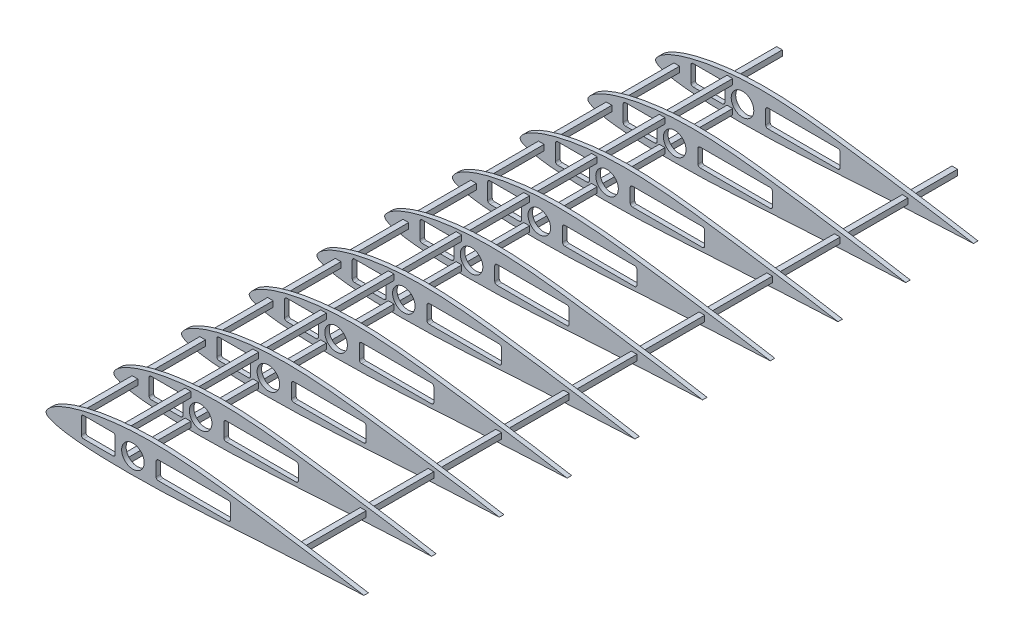
SolidWorks part; units mm, degrees
ref_plane "Front Plane" through (0, 0, 0) normal (0, 0, 1) x (1, 0, 0)
ref_plane "Top Plane" through (0, 0, 0) normal (0, 1, 0) x (1, 0, 0)
ref_plane "Right Plane" through (0, 0, 0) normal (1, 0, 0) x (0, 0, -1)
curve "Curve1"
  spline degree 3 poles (25.2088, 0.0031, 0) (25.4484, -0.0031, 0) (25.2117, 0.0209, 0) (25.0251, 0.0571, 0) (24.5852, 0.1328, 0) (24.06, 0.2322, 0) (23.3873, 0.3478, 0) (22.6018, 0.4739, 0) (21.7032, 0.6151, 0) (20.7068, 0.7694, 0) (19.6256, 0.9351, 0) (18.475, 1.1087, 0) (17.2708, 1.2865, 0) (16.0292, 1.4651, 0) (14.7666, 1.6379, 0) (13.5001, 1.8004, 0) (12.2446, 1.9439, 0) (11.0116, 2.0561, 0) (9.8099, 2.1301, 0) (8.6464, 2.1619, 0) (7.5276, 2.1493, 0) (6.459, 2.093, 0) (5.4467, 1.9949, 0) (4.4976, 1.8641, 0) (3.6202, 1.7053, 0) (2.8233, 1.523, 0) (2.1144, 1.3219, 0) (1.5008, 1.1059, 0) (0.9865, 0.8803, 0) (0.5779, 0.652, 0) (0.2708, 0.4245, 0) (0.0836, 0.2161, 0) (-0.0349, 0.004, 0) (0.089, -0.2027, 0) (0.3409, -0.3252, 0) (0.701, -0.4662, 0) (1.1913, -0.581, 0) (1.8002, -0.6841, 0) (2.5267, -0.768, 0) (3.3632, -0.8336, 0) (4.3022, -0.8807, 0) (5.334, -0.9092, 0) (6.4474, -0.9203, 0) (7.6302, -0.9134, 0) (8.8703, -0.8889, 0) (10.1572, -0.841, 0) (11.4808, -0.7741, 0) (12.8288, -0.6974, 0) (14.1854, -0.6164, 0) (15.5332, -0.5343, 0) (16.8545, -0.4545, 0) (18.1325, -0.3787, 0) (19.3501, -0.3089, 0) (20.4916, -0.2458, 0) (21.5411, -0.1904, 0) (22.4855, -0.1429, 0) (23.3092, -0.1017, 0) (24.0133, -0.0644, 0) (24.5612, -0.0287, 0) (25.0167, -0.0091, 0) (25.2088, 0.0031, 0) (25.4484, -0.0031, 0) (25.2117, 0.0209, 0) knots -0.015092 -0.006889 -0.001754 0 0.001748 0.006827 0.01488 0.025572 0.038694 0.054171 0.071834 0.091435 0.112685 0.135293 0.158944 0.183315 0.20807 0.232879 0.257399 0.281384 0.304706 0.327241 0.348897 0.369607 0.389308 0.407886 0.425177 0.441027 0.4553 0.467904 0.478752 0.487814 0.49509 0.500617 0.504451 0.507804 0.513091 0.520546 0.530249 0.542214 0.556382 0.572656 0.590895 0.610925 0.632536 0.655496 0.679547 0.704499 0.730211 0.756436 0.782837 0.809062 0.834776 0.859641 0.883338 0.905541 0.925965 0.944326 0.960366 0.973929 0.984908 0.993111 0.998246 1 1.001748 1.006827 1.01488 periodic
sketch "Sketch1" plane through (0, 0, 0) normal (0, 0, 1) x (1, 0, 0)
  line L0 (357.6496, 0) -> (0, 0) construction
  line L1 (0, 0) -> (0, 5.0209) construction
  spline S1 degree 3 poles (354.9573, 0.0431) (358.3317, -0.0432) (354.9981, 0.2938) (352.3707, 0.8024) (346.1763, 1.8676) (338.7813, 3.2655) (329.3081, 4.8919) (318.2482, 6.6648) (305.5952, 8.6507) (291.564, 10.8193) (276.34, 13.1505) (260.1392, 15.5903) (243.1815, 18.0913) (225.699, 20.6027) (207.9209, 23.0318) (190.087, 25.3152) (172.4086, 27.3328) (155.0467, 28.9096) (138.1258, 29.947) (121.7437, 30.3922) (105.9899, 30.2108) (90.9433, 29.4155) (76.6903, 28.0308) (63.3272, 26.1868) (50.9728, 23.9485) (39.7523, 21.3791) (29.7714, 18.545) (21.1318, 15.5018) (13.8914, 12.3237) (8.1391, 9.1075) (3.8158, 5.9031) (1.1802, 2.9693) (-0.4877, -0.018) (1.2572, -2.9285) (4.805, -4.6528) (9.8754, -6.6365) (16.78, -8.2511) (25.3535, -9.7017) (35.5828, -10.8813) (47.3622, -11.8027) (60.5842, -12.4624) (75.1117, -12.8607) (90.7897, -13.0132) (107.4435, -12.9137) (124.9052, -12.5651) (143.0256, -11.8868) (161.6617, -10.9405) (180.6424, -9.8572) (199.7442, -8.7119) (218.721, -7.5525) (237.3263, -6.4253) (255.3201, -5.3536) (272.4652, -4.367) (288.5372, -3.4753) (303.3148, -2.6922) (316.6121, -2.0207) (328.2104, -1.4385) (338.1246, -0.9102) (345.8395, -0.4061) (352.2525, -0.129) (354.9573, 0.0431) (358.3317, -0.0432) (354.9981, 0.2938) knots -0.015092 -0.006889 -0.001754 0 0.001748 0.006827 0.01488 0.025572 0.038694 0.054171 0.071834 0.091435 0.112685 0.135293 0.158944 0.183315 0.20807 0.232879 0.257399 0.281384 0.304706 0.327241 0.348897 0.369607 0.389308 0.407886 0.425177 0.441027 0.4553 0.467904 0.478752 0.487814 0.49509 0.500617 0.504451 0.507804 0.513091 0.520546 0.530249 0.542214 0.556382 0.572656 0.590895 0.610925 0.632536 0.655496 0.679547 0.704499 0.730211 0.756436 0.782837 0.809062 0.834776 0.859641 0.883338 0.905541 0.925965 0.944326 0.960366 0.973929 0.984908 0.993111 0.998246 1 1.001748 1.006827 1.01488 only from (357.6496, 0) to (357.6496, 0)
  dimension "D1" = 357.6496
ref_plane "Plane3" through (0, 0, 76.2) normal (0, 0, 1) x (1, 0, 0)
ref_plane "Plane4" through (0, 0, 152.4) normal (0, 0, 1) x (1, 0, 0)
ref_plane "Plane5" through (0, 0, 228.6) normal (0, 0, 1) x (1, 0, 0)
ref_plane "Plane6" through (0, 0, 304.8) normal (0, 0, 1) x (1, 0, 0)
ref_plane "Plane7" through (0, 0, 381) normal (0, 0, 1) x (1, 0, 0)
ref_plane "Plane8" through (0, 0, 457.2) normal (0, 0, 1) x (1, 0, 0)
ref_plane "Plane9" through (0, 0, 533.4) normal (0, 0, 1) x (1, 0, 0)
ref_plane "Plane10" through (0, 0, 609.6) normal (0, 0, 1) x (1, 0, 0)
ref_plane "Plane11" through (0, 0, 685.8) normal (0, 0, 1) x (1, 0, 0)
sketch "Sketch5" plane through (0, 0, 76.2) normal (0, 0, 1) x (1, 0, 0)
  spline S0 degree 3 poles (354.9573, 0.0431) (358.3317, -0.0432) (354.9981, 0.2938) (352.3707, 0.8024) (346.1763, 1.8676) (338.7813, 3.2655) (329.3081, 4.8919) (318.2482, 6.6648) (305.5952, 8.6507) (291.564, 10.8193) (276.34, 13.1505) (260.1392, 15.5903) (243.1815, 18.0913) (225.699, 20.6027) (207.9209, 23.0318) (190.087, 25.3152) (172.4086, 27.3328) (155.0467, 28.9096) (138.1258, 29.947) (121.7437, 30.3922) (105.9899, 30.2108) (90.9433, 29.4155) (76.6903, 28.0308) (63.3272, 26.1868) (50.9728, 23.9485) (39.7523, 21.3791) (29.7714, 18.545) (21.1318, 15.5018) (13.8914, 12.3237) (8.1391, 9.1075) (3.8158, 5.9031) (1.1802, 2.9693) (-0.4877, -0.018) (1.2572, -2.9285) (4.805, -4.6528) (9.8754, -6.6365) (16.78, -8.2511) (25.3535, -9.7017) (35.5828, -10.8813) (47.3622, -11.8027) (60.5842, -12.4624) (75.1117, -12.8607) (90.7897, -13.0132) (107.4435, -12.9137) (124.9052, -12.5651) (143.0256, -11.8868) (161.6617, -10.9405) (180.6424, -9.8572) (199.7442, -8.7119) (218.721, -7.5525) (237.3263, -6.4253) (255.3201, -5.3536) (272.4652, -4.367) (288.5372, -3.4753) (303.3148, -2.6922) (316.6121, -2.0207) (328.2104, -1.4385) (338.1246, -0.9102) (345.8395, -0.4061) (352.2525, -0.129) (354.9573, 0.0431) (358.3317, -0.0432) (354.9981, 0.2938) knots -0.015092 -0.006889 -0.001754 0 0.001748 0.006827 0.01488 0.025572 0.038694 0.054171 0.071834 0.091435 0.112685 0.135293 0.158944 0.183315 0.20807 0.232879 0.257399 0.281384 0.304706 0.327241 0.348897 0.369607 0.389308 0.407886 0.425177 0.441027 0.4553 0.467904 0.478752 0.487814 0.49509 0.500617 0.504451 0.507804 0.513091 0.520546 0.530249 0.542214 0.556382 0.572656 0.590895 0.610925 0.632536 0.655496 0.679547 0.704499 0.730211 0.756436 0.782837 0.809062 0.834776 0.859641 0.883338 0.905541 0.925965 0.944326 0.960366 0.973929 0.984908 0.993111 0.998246 1 1.001748 1.006827 1.01488 only from (357.6496, 0) to (357.6496, 0) construction
  spline S1 degree 3 poles (354.9573, 0.0431) (358.3317, -0.0432) (354.9981, 0.2938) (352.3707, 0.8024) (346.1763, 1.8676) (338.7813, 3.2655) (329.3081, 4.8919) (318.2482, 6.6648) (305.5952, 8.6507) (291.564, 10.8193) (276.34, 13.1505) (260.1392, 15.5903) (243.1815, 18.0913) (225.699, 20.6027) (207.9209, 23.0318) (190.087, 25.3152) (172.4086, 27.3328) (155.0467, 28.9096) (138.1258, 29.947) (121.7437, 30.3922) (105.9899, 30.2108) (90.9433, 29.4155) (76.6903, 28.0308) (63.3272, 26.1868) (50.9728, 23.9485) (39.7523, 21.3791) (29.7714, 18.545) (21.1318, 15.5018) (13.8914, 12.3237) (8.1391, 9.1075) (3.8158, 5.9031) (1.1802, 2.9693) (-0.4877, -0.018) (1.2572, -2.9285) (4.805, -4.6528) (9.8754, -6.6365) (16.78, -8.2511) (25.3535, -9.7017) (35.5828, -10.8813) (47.3622, -11.8027) (60.5842, -12.4624) (75.1117, -12.8607) (90.7897, -13.0132) (107.4435, -12.9137) (124.9052, -12.5651) (143.0256, -11.8868) (161.6617, -10.9405) (180.6424, -9.8572) (199.7442, -8.7119) (218.721, -7.5525) (237.3263, -6.4253) (255.3201, -5.3536) (272.4652, -4.367) (288.5372, -3.4753) (303.3148, -2.6922) (316.6121, -2.0207) (328.2104, -1.4385) (338.1246, -0.9102) (345.8395, -0.4061) (352.2525, -0.129) (354.9573, 0.0431) (358.3317, -0.0432) (354.9981, 0.2938) knots -0.015092 -0.006889 -0.001754 0 0.001748 0.006827 0.01488 0.025572 0.038694 0.054171 0.071834 0.091435 0.112685 0.135293 0.158944 0.183315 0.20807 0.232879 0.257399 0.281384 0.304706 0.327241 0.348897 0.369607 0.389308 0.407886 0.425177 0.441027 0.4553 0.467904 0.478752 0.487814 0.49509 0.500617 0.504451 0.507804 0.513091 0.520546 0.530249 0.542214 0.556382 0.572656 0.590895 0.610925 0.632536 0.655496 0.679547 0.704499 0.730211 0.756436 0.782837 0.809062 0.834776 0.859641 0.883338 0.905541 0.925965 0.944326 0.960366 0.973929 0.984908 0.993111 0.998246 1 1.001748 1.006827 1.01488 only from (357.6496, 0) to (357.6496, 0)
sketch "Sketch6" plane through (0, 0, 152.4) normal (0, 0, 1) x (1, 0, 0)
  spline S0 degree 3 poles (354.9573, 0.0431) (358.3317, -0.0432) (354.9981, 0.2938) (352.3707, 0.8024) (346.1763, 1.8676) (338.7813, 3.2655) (329.3081, 4.8919) (318.2482, 6.6648) (305.5952, 8.6507) (291.564, 10.8193) (276.34, 13.1505) (260.1392, 15.5903) (243.1815, 18.0913) (225.699, 20.6027) (207.9209, 23.0318) (190.087, 25.3152) (172.4086, 27.3328) (155.0467, 28.9096) (138.1258, 29.947) (121.7437, 30.3922) (105.9899, 30.2108) (90.9433, 29.4155) (76.6903, 28.0308) (63.3272, 26.1868) (50.9728, 23.9485) (39.7523, 21.3791) (29.7714, 18.545) (21.1318, 15.5018) (13.8914, 12.3237) (8.1391, 9.1075) (3.8158, 5.9031) (1.1802, 2.9693) (-0.4877, -0.018) (1.2572, -2.9285) (4.805, -4.6528) (9.8754, -6.6365) (16.78, -8.2511) (25.3535, -9.7017) (35.5828, -10.8813) (47.3622, -11.8027) (60.5842, -12.4624) (75.1117, -12.8607) (90.7897, -13.0132) (107.4435, -12.9137) (124.9052, -12.5651) (143.0256, -11.8868) (161.6617, -10.9405) (180.6424, -9.8572) (199.7442, -8.7119) (218.721, -7.5525) (237.3263, -6.4253) (255.3201, -5.3536) (272.4652, -4.367) (288.5372, -3.4753) (303.3148, -2.6922) (316.6121, -2.0207) (328.2104, -1.4385) (338.1246, -0.9102) (345.8395, -0.4061) (352.2525, -0.129) (354.9573, 0.0431) (358.3317, -0.0432) (354.9981, 0.2938) knots -0.015092 -0.006889 -0.001754 0 0.001748 0.006827 0.01488 0.025572 0.038694 0.054171 0.071834 0.091435 0.112685 0.135293 0.158944 0.183315 0.20807 0.232879 0.257399 0.281384 0.304706 0.327241 0.348897 0.369607 0.389308 0.407886 0.425177 0.441027 0.4553 0.467904 0.478752 0.487814 0.49509 0.500617 0.504451 0.507804 0.513091 0.520546 0.530249 0.542214 0.556382 0.572656 0.590895 0.610925 0.632536 0.655496 0.679547 0.704499 0.730211 0.756436 0.782837 0.809062 0.834776 0.859641 0.883338 0.905541 0.925965 0.944326 0.960366 0.973929 0.984908 0.993111 0.998246 1 1.001748 1.006827 1.01488 only from (357.6496, 0) to (357.6496, 0) construction
  spline S1 degree 3 poles (354.9573, 0.0431) (358.3317, -0.0432) (354.9981, 0.2938) (352.3707, 0.8024) (346.1763, 1.8676) (338.7813, 3.2655) (329.3081, 4.8919) (318.2482, 6.6648) (305.5952, 8.6507) (291.564, 10.8193) (276.34, 13.1505) (260.1392, 15.5903) (243.1815, 18.0913) (225.699, 20.6027) (207.9209, 23.0318) (190.087, 25.3152) (172.4086, 27.3328) (155.0467, 28.9096) (138.1258, 29.947) (121.7437, 30.3922) (105.9899, 30.2108) (90.9433, 29.4155) (76.6903, 28.0308) (63.3272, 26.1868) (50.9728, 23.9485) (39.7523, 21.3791) (29.7714, 18.545) (21.1318, 15.5018) (13.8914, 12.3237) (8.1391, 9.1075) (3.8158, 5.9031) (1.1802, 2.9693) (-0.4877, -0.018) (1.2572, -2.9285) (4.805, -4.6528) (9.8754, -6.6365) (16.78, -8.2511) (25.3535, -9.7017) (35.5828, -10.8813) (47.3622, -11.8027) (60.5842, -12.4624) (75.1117, -12.8607) (90.7897, -13.0132) (107.4435, -12.9137) (124.9052, -12.5651) (143.0256, -11.8868) (161.6617, -10.9405) (180.6424, -9.8572) (199.7442, -8.7119) (218.721, -7.5525) (237.3263, -6.4253) (255.3201, -5.3536) (272.4652, -4.367) (288.5372, -3.4753) (303.3148, -2.6922) (316.6121, -2.0207) (328.2104, -1.4385) (338.1246, -0.9102) (345.8395, -0.4061) (352.2525, -0.129) (354.9573, 0.0431) (358.3317, -0.0432) (354.9981, 0.2938) knots -0.015092 -0.006889 -0.001754 0 0.001748 0.006827 0.01488 0.025572 0.038694 0.054171 0.071834 0.091435 0.112685 0.135293 0.158944 0.183315 0.20807 0.232879 0.257399 0.281384 0.304706 0.327241 0.348897 0.369607 0.389308 0.407886 0.425177 0.441027 0.4553 0.467904 0.478752 0.487814 0.49509 0.500617 0.504451 0.507804 0.513091 0.520546 0.530249 0.542214 0.556382 0.572656 0.590895 0.610925 0.632536 0.655496 0.679547 0.704499 0.730211 0.756436 0.782837 0.809062 0.834776 0.859641 0.883338 0.905541 0.925965 0.944326 0.960366 0.973929 0.984908 0.993111 0.998246 1 1.001748 1.006827 1.01488 only from (357.6496, 0) to (357.6496, 0)
sketch "Sketch7" plane through (0, 0, 228.6) normal (0, 0, 1) x (1, 0, 0)
  spline S0 degree 3 poles (354.9573, 0.0431) (358.3317, -0.0432) (354.9981, 0.2938) (352.3707, 0.8024) (346.1763, 1.8676) (338.7813, 3.2655) (329.3081, 4.8919) (318.2482, 6.6648) (305.5952, 8.6507) (291.564, 10.8193) (276.34, 13.1505) (260.1392, 15.5903) (243.1815, 18.0913) (225.699, 20.6027) (207.9209, 23.0318) (190.087, 25.3152) (172.4086, 27.3328) (155.0467, 28.9096) (138.1258, 29.947) (121.7437, 30.3922) (105.9899, 30.2108) (90.9433, 29.4155) (76.6903, 28.0308) (63.3272, 26.1868) (50.9728, 23.9485) (39.7523, 21.3791) (29.7714, 18.545) (21.1318, 15.5018) (13.8914, 12.3237) (8.1391, 9.1075) (3.8158, 5.9031) (1.1802, 2.9693) (-0.4877, -0.018) (1.2572, -2.9285) (4.805, -4.6528) (9.8754, -6.6365) (16.78, -8.2511) (25.3535, -9.7017) (35.5828, -10.8813) (47.3622, -11.8027) (60.5842, -12.4624) (75.1117, -12.8607) (90.7897, -13.0132) (107.4435, -12.9137) (124.9052, -12.5651) (143.0256, -11.8868) (161.6617, -10.9405) (180.6424, -9.8572) (199.7442, -8.7119) (218.721, -7.5525) (237.3263, -6.4253) (255.3201, -5.3536) (272.4652, -4.367) (288.5372, -3.4753) (303.3148, -2.6922) (316.6121, -2.0207) (328.2104, -1.4385) (338.1246, -0.9102) (345.8395, -0.4061) (352.2525, -0.129) (354.9573, 0.0431) (358.3317, -0.0432) (354.9981, 0.2938) knots -0.015092 -0.006889 -0.001754 0 0.001748 0.006827 0.01488 0.025572 0.038694 0.054171 0.071834 0.091435 0.112685 0.135293 0.158944 0.183315 0.20807 0.232879 0.257399 0.281384 0.304706 0.327241 0.348897 0.369607 0.389308 0.407886 0.425177 0.441027 0.4553 0.467904 0.478752 0.487814 0.49509 0.500617 0.504451 0.507804 0.513091 0.520546 0.530249 0.542214 0.556382 0.572656 0.590895 0.610925 0.632536 0.655496 0.679547 0.704499 0.730211 0.756436 0.782837 0.809062 0.834776 0.859641 0.883338 0.905541 0.925965 0.944326 0.960366 0.973929 0.984908 0.993111 0.998246 1 1.001748 1.006827 1.01488 only from (357.6496, 0) to (357.6496, 0) construction
  spline S1 degree 3 poles (354.9573, 0.0431) (358.3317, -0.0432) (354.9981, 0.2938) (352.3707, 0.8024) (346.1763, 1.8676) (338.7813, 3.2655) (329.3081, 4.8919) (318.2482, 6.6648) (305.5952, 8.6507) (291.564, 10.8193) (276.34, 13.1505) (260.1392, 15.5903) (243.1815, 18.0913) (225.699, 20.6027) (207.9209, 23.0318) (190.087, 25.3152) (172.4086, 27.3328) (155.0467, 28.9096) (138.1258, 29.947) (121.7437, 30.3922) (105.9899, 30.2108) (90.9433, 29.4155) (76.6903, 28.0308) (63.3272, 26.1868) (50.9728, 23.9485) (39.7523, 21.3791) (29.7714, 18.545) (21.1318, 15.5018) (13.8914, 12.3237) (8.1391, 9.1075) (3.8158, 5.9031) (1.1802, 2.9693) (-0.4877, -0.018) (1.2572, -2.9285) (4.805, -4.6528) (9.8754, -6.6365) (16.78, -8.2511) (25.3535, -9.7017) (35.5828, -10.8813) (47.3622, -11.8027) (60.5842, -12.4624) (75.1117, -12.8607) (90.7897, -13.0132) (107.4435, -12.9137) (124.9052, -12.5651) (143.0256, -11.8868) (161.6617, -10.9405) (180.6424, -9.8572) (199.7442, -8.7119) (218.721, -7.5525) (237.3263, -6.4253) (255.3201, -5.3536) (272.4652, -4.367) (288.5372, -3.4753) (303.3148, -2.6922) (316.6121, -2.0207) (328.2104, -1.4385) (338.1246, -0.9102) (345.8395, -0.4061) (352.2525, -0.129) (354.9573, 0.0431) (358.3317, -0.0432) (354.9981, 0.2938) knots -0.015092 -0.006889 -0.001754 0 0.001748 0.006827 0.01488 0.025572 0.038694 0.054171 0.071834 0.091435 0.112685 0.135293 0.158944 0.183315 0.20807 0.232879 0.257399 0.281384 0.304706 0.327241 0.348897 0.369607 0.389308 0.407886 0.425177 0.441027 0.4553 0.467904 0.478752 0.487814 0.49509 0.500617 0.504451 0.507804 0.513091 0.520546 0.530249 0.542214 0.556382 0.572656 0.590895 0.610925 0.632536 0.655496 0.679547 0.704499 0.730211 0.756436 0.782837 0.809062 0.834776 0.859641 0.883338 0.905541 0.925965 0.944326 0.960366 0.973929 0.984908 0.993111 0.998246 1 1.001748 1.006827 1.01488 only from (357.6496, 0) to (357.6496, 0)
sketch "Sketch8" plane through (0, 0, 304.8) normal (0, 0, 1) x (1, 0, 0)
  spline S0 degree 3 poles (354.9573, 0.0431) (358.3317, -0.0432) (354.9981, 0.2938) (352.3707, 0.8024) (346.1763, 1.8676) (338.7813, 3.2655) (329.3081, 4.8919) (318.2482, 6.6648) (305.5952, 8.6507) (291.564, 10.8193) (276.34, 13.1505) (260.1392, 15.5903) (243.1815, 18.0913) (225.699, 20.6027) (207.9209, 23.0318) (190.087, 25.3152) (172.4086, 27.3328) (155.0467, 28.9096) (138.1258, 29.947) (121.7437, 30.3922) (105.9899, 30.2108) (90.9433, 29.4155) (76.6903, 28.0308) (63.3272, 26.1868) (50.9728, 23.9485) (39.7523, 21.3791) (29.7714, 18.545) (21.1318, 15.5018) (13.8914, 12.3237) (8.1391, 9.1075) (3.8158, 5.9031) (1.1802, 2.9693) (-0.4877, -0.018) (1.2572, -2.9285) (4.805, -4.6528) (9.8754, -6.6365) (16.78, -8.2511) (25.3535, -9.7017) (35.5828, -10.8813) (47.3622, -11.8027) (60.5842, -12.4624) (75.1117, -12.8607) (90.7897, -13.0132) (107.4435, -12.9137) (124.9052, -12.5651) (143.0256, -11.8868) (161.6617, -10.9405) (180.6424, -9.8572) (199.7442, -8.7119) (218.721, -7.5525) (237.3263, -6.4253) (255.3201, -5.3536) (272.4652, -4.367) (288.5372, -3.4753) (303.3148, -2.6922) (316.6121, -2.0207) (328.2104, -1.4385) (338.1246, -0.9102) (345.8395, -0.4061) (352.2525, -0.129) (354.9573, 0.0431) (358.3317, -0.0432) (354.9981, 0.2938) knots -0.015092 -0.006889 -0.001754 0 0.001748 0.006827 0.01488 0.025572 0.038694 0.054171 0.071834 0.091435 0.112685 0.135293 0.158944 0.183315 0.20807 0.232879 0.257399 0.281384 0.304706 0.327241 0.348897 0.369607 0.389308 0.407886 0.425177 0.441027 0.4553 0.467904 0.478752 0.487814 0.49509 0.500617 0.504451 0.507804 0.513091 0.520546 0.530249 0.542214 0.556382 0.572656 0.590895 0.610925 0.632536 0.655496 0.679547 0.704499 0.730211 0.756436 0.782837 0.809062 0.834776 0.859641 0.883338 0.905541 0.925965 0.944326 0.960366 0.973929 0.984908 0.993111 0.998246 1 1.001748 1.006827 1.01488 only from (357.6496, 0) to (357.6496, 0) construction
  spline S1 degree 3 poles (354.9573, 0.0431) (358.3317, -0.0432) (354.9981, 0.2938) (352.3707, 0.8024) (346.1763, 1.8676) (338.7813, 3.2655) (329.3081, 4.8919) (318.2482, 6.6648) (305.5952, 8.6507) (291.564, 10.8193) (276.34, 13.1505) (260.1392, 15.5903) (243.1815, 18.0913) (225.699, 20.6027) (207.9209, 23.0318) (190.087, 25.3152) (172.4086, 27.3328) (155.0467, 28.9096) (138.1258, 29.947) (121.7437, 30.3922) (105.9899, 30.2108) (90.9433, 29.4155) (76.6903, 28.0308) (63.3272, 26.1868) (50.9728, 23.9485) (39.7523, 21.3791) (29.7714, 18.545) (21.1318, 15.5018) (13.8914, 12.3237) (8.1391, 9.1075) (3.8158, 5.9031) (1.1802, 2.9693) (-0.4877, -0.018) (1.2572, -2.9285) (4.805, -4.6528) (9.8754, -6.6365) (16.78, -8.2511) (25.3535, -9.7017) (35.5828, -10.8813) (47.3622, -11.8027) (60.5842, -12.4624) (75.1117, -12.8607) (90.7897, -13.0132) (107.4435, -12.9137) (124.9052, -12.5651) (143.0256, -11.8868) (161.6617, -10.9405) (180.6424, -9.8572) (199.7442, -8.7119) (218.721, -7.5525) (237.3263, -6.4253) (255.3201, -5.3536) (272.4652, -4.367) (288.5372, -3.4753) (303.3148, -2.6922) (316.6121, -2.0207) (328.2104, -1.4385) (338.1246, -0.9102) (345.8395, -0.4061) (352.2525, -0.129) (354.9573, 0.0431) (358.3317, -0.0432) (354.9981, 0.2938) knots -0.015092 -0.006889 -0.001754 0 0.001748 0.006827 0.01488 0.025572 0.038694 0.054171 0.071834 0.091435 0.112685 0.135293 0.158944 0.183315 0.20807 0.232879 0.257399 0.281384 0.304706 0.327241 0.348897 0.369607 0.389308 0.407886 0.425177 0.441027 0.4553 0.467904 0.478752 0.487814 0.49509 0.500617 0.504451 0.507804 0.513091 0.520546 0.530249 0.542214 0.556382 0.572656 0.590895 0.610925 0.632536 0.655496 0.679547 0.704499 0.730211 0.756436 0.782837 0.809062 0.834776 0.859641 0.883338 0.905541 0.925965 0.944326 0.960366 0.973929 0.984908 0.993111 0.998246 1 1.001748 1.006827 1.01488 only from (357.6496, 0) to (357.6496, 0)
sketch "Sketch9" plane through (0, 0, 381) normal (0, 0, 1) x (1, 0, 0)
  spline S0 degree 3 poles (354.9573, 0.0431) (358.3317, -0.0432) (354.9981, 0.2938) (352.3707, 0.8024) (346.1763, 1.8676) (338.7813, 3.2655) (329.3081, 4.8919) (318.2482, 6.6648) (305.5952, 8.6507) (291.564, 10.8193) (276.34, 13.1505) (260.1392, 15.5903) (243.1815, 18.0913) (225.699, 20.6027) (207.9209, 23.0318) (190.087, 25.3152) (172.4086, 27.3328) (155.0467, 28.9096) (138.1258, 29.947) (121.7437, 30.3922) (105.9899, 30.2108) (90.9433, 29.4155) (76.6903, 28.0308) (63.3272, 26.1868) (50.9728, 23.9485) (39.7523, 21.3791) (29.7714, 18.545) (21.1318, 15.5018) (13.8914, 12.3237) (8.1391, 9.1075) (3.8158, 5.9031) (1.1802, 2.9693) (-0.4877, -0.018) (1.2572, -2.9285) (4.805, -4.6528) (9.8754, -6.6365) (16.78, -8.2511) (25.3535, -9.7017) (35.5828, -10.8813) (47.3622, -11.8027) (60.5842, -12.4624) (75.1117, -12.8607) (90.7897, -13.0132) (107.4435, -12.9137) (124.9052, -12.5651) (143.0256, -11.8868) (161.6617, -10.9405) (180.6424, -9.8572) (199.7442, -8.7119) (218.721, -7.5525) (237.3263, -6.4253) (255.3201, -5.3536) (272.4652, -4.367) (288.5372, -3.4753) (303.3148, -2.6922) (316.6121, -2.0207) (328.2104, -1.4385) (338.1246, -0.9102) (345.8395, -0.4061) (352.2525, -0.129) (354.9573, 0.0431) (358.3317, -0.0432) (354.9981, 0.2938) knots -0.015092 -0.006889 -0.001754 0 0.001748 0.006827 0.01488 0.025572 0.038694 0.054171 0.071834 0.091435 0.112685 0.135293 0.158944 0.183315 0.20807 0.232879 0.257399 0.281384 0.304706 0.327241 0.348897 0.369607 0.389308 0.407886 0.425177 0.441027 0.4553 0.467904 0.478752 0.487814 0.49509 0.500617 0.504451 0.507804 0.513091 0.520546 0.530249 0.542214 0.556382 0.572656 0.590895 0.610925 0.632536 0.655496 0.679547 0.704499 0.730211 0.756436 0.782837 0.809062 0.834776 0.859641 0.883338 0.905541 0.925965 0.944326 0.960366 0.973929 0.984908 0.993111 0.998246 1 1.001748 1.006827 1.01488 only from (357.6496, 0) to (357.6496, 0) construction
  spline S1 degree 3 poles (354.9573, 0.0431) (358.3317, -0.0432) (354.9981, 0.2938) (352.3707, 0.8024) (346.1763, 1.8676) (338.7813, 3.2655) (329.3081, 4.8919) (318.2482, 6.6648) (305.5952, 8.6507) (291.564, 10.8193) (276.34, 13.1505) (260.1392, 15.5903) (243.1815, 18.0913) (225.699, 20.6027) (207.9209, 23.0318) (190.087, 25.3152) (172.4086, 27.3328) (155.0467, 28.9096) (138.1258, 29.947) (121.7437, 30.3922) (105.9899, 30.2108) (90.9433, 29.4155) (76.6903, 28.0308) (63.3272, 26.1868) (50.9728, 23.9485) (39.7523, 21.3791) (29.7714, 18.545) (21.1318, 15.5018) (13.8914, 12.3237) (8.1391, 9.1075) (3.8158, 5.9031) (1.1802, 2.9693) (-0.4877, -0.018) (1.2572, -2.9285) (4.805, -4.6528) (9.8754, -6.6365) (16.78, -8.2511) (25.3535, -9.7017) (35.5828, -10.8813) (47.3622, -11.8027) (60.5842, -12.4624) (75.1117, -12.8607) (90.7897, -13.0132) (107.4435, -12.9137) (124.9052, -12.5651) (143.0256, -11.8868) (161.6617, -10.9405) (180.6424, -9.8572) (199.7442, -8.7119) (218.721, -7.5525) (237.3263, -6.4253) (255.3201, -5.3536) (272.4652, -4.367) (288.5372, -3.4753) (303.3148, -2.6922) (316.6121, -2.0207) (328.2104, -1.4385) (338.1246, -0.9102) (345.8395, -0.4061) (352.2525, -0.129) (354.9573, 0.0431) (358.3317, -0.0432) (354.9981, 0.2938) knots -0.015092 -0.006889 -0.001754 0 0.001748 0.006827 0.01488 0.025572 0.038694 0.054171 0.071834 0.091435 0.112685 0.135293 0.158944 0.183315 0.20807 0.232879 0.257399 0.281384 0.304706 0.327241 0.348897 0.369607 0.389308 0.407886 0.425177 0.441027 0.4553 0.467904 0.478752 0.487814 0.49509 0.500617 0.504451 0.507804 0.513091 0.520546 0.530249 0.542214 0.556382 0.572656 0.590895 0.610925 0.632536 0.655496 0.679547 0.704499 0.730211 0.756436 0.782837 0.809062 0.834776 0.859641 0.883338 0.905541 0.925965 0.944326 0.960366 0.973929 0.984908 0.993111 0.998246 1 1.001748 1.006827 1.01488 only from (357.6496, 0) to (357.6496, 0)
sketch "Sketch10" plane through (0, 0, 457.2) normal (0, 0, 1) x (1, 0, 0)
  spline S0 degree 3 poles (354.9573, 0.0431) (358.3317, -0.0432) (354.9981, 0.2938) (352.3707, 0.8024) (346.1763, 1.8676) (338.7813, 3.2655) (329.3081, 4.8919) (318.2482, 6.6648) (305.5952, 8.6507) (291.564, 10.8193) (276.34, 13.1505) (260.1392, 15.5903) (243.1815, 18.0913) (225.699, 20.6027) (207.9209, 23.0318) (190.087, 25.3152) (172.4086, 27.3328) (155.0467, 28.9096) (138.1258, 29.947) (121.7437, 30.3922) (105.9899, 30.2108) (90.9433, 29.4155) (76.6903, 28.0308) (63.3272, 26.1868) (50.9728, 23.9485) (39.7523, 21.3791) (29.7714, 18.545) (21.1318, 15.5018) (13.8914, 12.3237) (8.1391, 9.1075) (3.8158, 5.9031) (1.1802, 2.9693) (-0.4877, -0.018) (1.2572, -2.9285) (4.805, -4.6528) (9.8754, -6.6365) (16.78, -8.2511) (25.3535, -9.7017) (35.5828, -10.8813) (47.3622, -11.8027) (60.5842, -12.4624) (75.1117, -12.8607) (90.7897, -13.0132) (107.4435, -12.9137) (124.9052, -12.5651) (143.0256, -11.8868) (161.6617, -10.9405) (180.6424, -9.8572) (199.7442, -8.7119) (218.721, -7.5525) (237.3263, -6.4253) (255.3201, -5.3536) (272.4652, -4.367) (288.5372, -3.4753) (303.3148, -2.6922) (316.6121, -2.0207) (328.2104, -1.4385) (338.1246, -0.9102) (345.8395, -0.4061) (352.2525, -0.129) (354.9573, 0.0431) (358.3317, -0.0432) (354.9981, 0.2938) knots -0.015092 -0.006889 -0.001754 0 0.001748 0.006827 0.01488 0.025572 0.038694 0.054171 0.071834 0.091435 0.112685 0.135293 0.158944 0.183315 0.20807 0.232879 0.257399 0.281384 0.304706 0.327241 0.348897 0.369607 0.389308 0.407886 0.425177 0.441027 0.4553 0.467904 0.478752 0.487814 0.49509 0.500617 0.504451 0.507804 0.513091 0.520546 0.530249 0.542214 0.556382 0.572656 0.590895 0.610925 0.632536 0.655496 0.679547 0.704499 0.730211 0.756436 0.782837 0.809062 0.834776 0.859641 0.883338 0.905541 0.925965 0.944326 0.960366 0.973929 0.984908 0.993111 0.998246 1 1.001748 1.006827 1.01488 only from (357.6496, 0) to (357.6496, 0) construction
  spline S1 degree 3 poles (354.9573, 0.0431) (358.3317, -0.0432) (354.9981, 0.2938) (352.3707, 0.8024) (346.1763, 1.8676) (338.7813, 3.2655) (329.3081, 4.8919) (318.2482, 6.6648) (305.5952, 8.6507) (291.564, 10.8193) (276.34, 13.1505) (260.1392, 15.5903) (243.1815, 18.0913) (225.699, 20.6027) (207.9209, 23.0318) (190.087, 25.3152) (172.4086, 27.3328) (155.0467, 28.9096) (138.1258, 29.947) (121.7437, 30.3922) (105.9899, 30.2108) (90.9433, 29.4155) (76.6903, 28.0308) (63.3272, 26.1868) (50.9728, 23.9485) (39.7523, 21.3791) (29.7714, 18.545) (21.1318, 15.5018) (13.8914, 12.3237) (8.1391, 9.1075) (3.8158, 5.9031) (1.1802, 2.9693) (-0.4877, -0.018) (1.2572, -2.9285) (4.805, -4.6528) (9.8754, -6.6365) (16.78, -8.2511) (25.3535, -9.7017) (35.5828, -10.8813) (47.3622, -11.8027) (60.5842, -12.4624) (75.1117, -12.8607) (90.7897, -13.0132) (107.4435, -12.9137) (124.9052, -12.5651) (143.0256, -11.8868) (161.6617, -10.9405) (180.6424, -9.8572) (199.7442, -8.7119) (218.721, -7.5525) (237.3263, -6.4253) (255.3201, -5.3536) (272.4652, -4.367) (288.5372, -3.4753) (303.3148, -2.6922) (316.6121, -2.0207) (328.2104, -1.4385) (338.1246, -0.9102) (345.8395, -0.4061) (352.2525, -0.129) (354.9573, 0.0431) (358.3317, -0.0432) (354.9981, 0.2938) knots -0.015092 -0.006889 -0.001754 0 0.001748 0.006827 0.01488 0.025572 0.038694 0.054171 0.071834 0.091435 0.112685 0.135293 0.158944 0.183315 0.20807 0.232879 0.257399 0.281384 0.304706 0.327241 0.348897 0.369607 0.389308 0.407886 0.425177 0.441027 0.4553 0.467904 0.478752 0.487814 0.49509 0.500617 0.504451 0.507804 0.513091 0.520546 0.530249 0.542214 0.556382 0.572656 0.590895 0.610925 0.632536 0.655496 0.679547 0.704499 0.730211 0.756436 0.782837 0.809062 0.834776 0.859641 0.883338 0.905541 0.925965 0.944326 0.960366 0.973929 0.984908 0.993111 0.998246 1 1.001748 1.006827 1.01488 only from (357.6496, 0) to (357.6496, 0)
sketch "Sketch11" plane through (0, 0, 533.4) normal (0, 0, 1) x (1, 0, 0)
  spline S0 degree 3 poles (354.9573, 0.0431) (358.3317, -0.0432) (354.9981, 0.2938) (352.3707, 0.8024) (346.1763, 1.8676) (338.7813, 3.2655) (329.3081, 4.8919) (318.2482, 6.6648) (305.5952, 8.6507) (291.564, 10.8193) (276.34, 13.1505) (260.1392, 15.5903) (243.1815, 18.0913) (225.699, 20.6027) (207.9209, 23.0318) (190.087, 25.3152) (172.4086, 27.3328) (155.0467, 28.9096) (138.1258, 29.947) (121.7437, 30.3922) (105.9899, 30.2108) (90.9433, 29.4155) (76.6903, 28.0308) (63.3272, 26.1868) (50.9728, 23.9485) (39.7523, 21.3791) (29.7714, 18.545) (21.1318, 15.5018) (13.8914, 12.3237) (8.1391, 9.1075) (3.8158, 5.9031) (1.1802, 2.9693) (-0.4877, -0.018) (1.2572, -2.9285) (4.805, -4.6528) (9.8754, -6.6365) (16.78, -8.2511) (25.3535, -9.7017) (35.5828, -10.8813) (47.3622, -11.8027) (60.5842, -12.4624) (75.1117, -12.8607) (90.7897, -13.0132) (107.4435, -12.9137) (124.9052, -12.5651) (143.0256, -11.8868) (161.6617, -10.9405) (180.6424, -9.8572) (199.7442, -8.7119) (218.721, -7.5525) (237.3263, -6.4253) (255.3201, -5.3536) (272.4652, -4.367) (288.5372, -3.4753) (303.3148, -2.6922) (316.6121, -2.0207) (328.2104, -1.4385) (338.1246, -0.9102) (345.8395, -0.4061) (352.2525, -0.129) (354.9573, 0.0431) (358.3317, -0.0432) (354.9981, 0.2938) knots -0.015092 -0.006889 -0.001754 0 0.001748 0.006827 0.01488 0.025572 0.038694 0.054171 0.071834 0.091435 0.112685 0.135293 0.158944 0.183315 0.20807 0.232879 0.257399 0.281384 0.304706 0.327241 0.348897 0.369607 0.389308 0.407886 0.425177 0.441027 0.4553 0.467904 0.478752 0.487814 0.49509 0.500617 0.504451 0.507804 0.513091 0.520546 0.530249 0.542214 0.556382 0.572656 0.590895 0.610925 0.632536 0.655496 0.679547 0.704499 0.730211 0.756436 0.782837 0.809062 0.834776 0.859641 0.883338 0.905541 0.925965 0.944326 0.960366 0.973929 0.984908 0.993111 0.998246 1 1.001748 1.006827 1.01488 only from (357.6496, 0) to (357.6496, 0) construction
  spline S1 degree 3 poles (354.9573, 0.0431) (358.3317, -0.0432) (354.9981, 0.2938) (352.3707, 0.8024) (346.1763, 1.8676) (338.7813, 3.2655) (329.3081, 4.8919) (318.2482, 6.6648) (305.5952, 8.6507) (291.564, 10.8193) (276.34, 13.1505) (260.1392, 15.5903) (243.1815, 18.0913) (225.699, 20.6027) (207.9209, 23.0318) (190.087, 25.3152) (172.4086, 27.3328) (155.0467, 28.9096) (138.1258, 29.947) (121.7437, 30.3922) (105.9899, 30.2108) (90.9433, 29.4155) (76.6903, 28.0308) (63.3272, 26.1868) (50.9728, 23.9485) (39.7523, 21.3791) (29.7714, 18.545) (21.1318, 15.5018) (13.8914, 12.3237) (8.1391, 9.1075) (3.8158, 5.9031) (1.1802, 2.9693) (-0.4877, -0.018) (1.2572, -2.9285) (4.805, -4.6528) (9.8754, -6.6365) (16.78, -8.2511) (25.3535, -9.7017) (35.5828, -10.8813) (47.3622, -11.8027) (60.5842, -12.4624) (75.1117, -12.8607) (90.7897, -13.0132) (107.4435, -12.9137) (124.9052, -12.5651) (143.0256, -11.8868) (161.6617, -10.9405) (180.6424, -9.8572) (199.7442, -8.7119) (218.721, -7.5525) (237.3263, -6.4253) (255.3201, -5.3536) (272.4652, -4.367) (288.5372, -3.4753) (303.3148, -2.6922) (316.6121, -2.0207) (328.2104, -1.4385) (338.1246, -0.9102) (345.8395, -0.4061) (352.2525, -0.129) (354.9573, 0.0431) (358.3317, -0.0432) (354.9981, 0.2938) knots -0.015092 -0.006889 -0.001754 0 0.001748 0.006827 0.01488 0.025572 0.038694 0.054171 0.071834 0.091435 0.112685 0.135293 0.158944 0.183315 0.20807 0.232879 0.257399 0.281384 0.304706 0.327241 0.348897 0.369607 0.389308 0.407886 0.425177 0.441027 0.4553 0.467904 0.478752 0.487814 0.49509 0.500617 0.504451 0.507804 0.513091 0.520546 0.530249 0.542214 0.556382 0.572656 0.590895 0.610925 0.632536 0.655496 0.679547 0.704499 0.730211 0.756436 0.782837 0.809062 0.834776 0.859641 0.883338 0.905541 0.925965 0.944326 0.960366 0.973929 0.984908 0.993111 0.998246 1 1.001748 1.006827 1.01488 only from (357.6496, 0) to (357.6496, 0)
sketch "Sketch12" plane through (0, 0, 609.6) normal (0, 0, 1) x (1, 0, 0)
  spline S0 degree 3 poles (354.9573, 0.0431) (358.3317, -0.0432) (354.9981, 0.2938) (352.3707, 0.8024) (346.1763, 1.8676) (338.7813, 3.2655) (329.3081, 4.8919) (318.2482, 6.6648) (305.5952, 8.6507) (291.564, 10.8193) (276.34, 13.1505) (260.1392, 15.5903) (243.1815, 18.0913) (225.699, 20.6027) (207.9209, 23.0318) (190.087, 25.3152) (172.4086, 27.3328) (155.0467, 28.9096) (138.1258, 29.947) (121.7437, 30.3922) (105.9899, 30.2108) (90.9433, 29.4155) (76.6903, 28.0308) (63.3272, 26.1868) (50.9728, 23.9485) (39.7523, 21.3791) (29.7714, 18.545) (21.1318, 15.5018) (13.8914, 12.3237) (8.1391, 9.1075) (3.8158, 5.9031) (1.1802, 2.9693) (-0.4877, -0.018) (1.2572, -2.9285) (4.805, -4.6528) (9.8754, -6.6365) (16.78, -8.2511) (25.3535, -9.7017) (35.5828, -10.8813) (47.3622, -11.8027) (60.5842, -12.4624) (75.1117, -12.8607) (90.7897, -13.0132) (107.4435, -12.9137) (124.9052, -12.5651) (143.0256, -11.8868) (161.6617, -10.9405) (180.6424, -9.8572) (199.7442, -8.7119) (218.721, -7.5525) (237.3263, -6.4253) (255.3201, -5.3536) (272.4652, -4.367) (288.5372, -3.4753) (303.3148, -2.6922) (316.6121, -2.0207) (328.2104, -1.4385) (338.1246, -0.9102) (345.8395, -0.4061) (352.2525, -0.129) (354.9573, 0.0431) (358.3317, -0.0432) (354.9981, 0.2938) knots -0.015092 -0.006889 -0.001754 0 0.001748 0.006827 0.01488 0.025572 0.038694 0.054171 0.071834 0.091435 0.112685 0.135293 0.158944 0.183315 0.20807 0.232879 0.257399 0.281384 0.304706 0.327241 0.348897 0.369607 0.389308 0.407886 0.425177 0.441027 0.4553 0.467904 0.478752 0.487814 0.49509 0.500617 0.504451 0.507804 0.513091 0.520546 0.530249 0.542214 0.556382 0.572656 0.590895 0.610925 0.632536 0.655496 0.679547 0.704499 0.730211 0.756436 0.782837 0.809062 0.834776 0.859641 0.883338 0.905541 0.925965 0.944326 0.960366 0.973929 0.984908 0.993111 0.998246 1 1.001748 1.006827 1.01488 only from (357.6496, 0) to (357.6496, 0) construction
  spline S1 degree 3 poles (354.9573, 0.0431) (358.3317, -0.0432) (354.9981, 0.2938) (352.3707, 0.8024) (346.1763, 1.8676) (338.7813, 3.2655) (329.3081, 4.8919) (318.2482, 6.6648) (305.5952, 8.6507) (291.564, 10.8193) (276.34, 13.1505) (260.1392, 15.5903) (243.1815, 18.0913) (225.699, 20.6027) (207.9209, 23.0318) (190.087, 25.3152) (172.4086, 27.3328) (155.0467, 28.9096) (138.1258, 29.947) (121.7437, 30.3922) (105.9899, 30.2108) (90.9433, 29.4155) (76.6903, 28.0308) (63.3272, 26.1868) (50.9728, 23.9485) (39.7523, 21.3791) (29.7714, 18.545) (21.1318, 15.5018) (13.8914, 12.3237) (8.1391, 9.1075) (3.8158, 5.9031) (1.1802, 2.9693) (-0.4877, -0.018) (1.2572, -2.9285) (4.805, -4.6528) (9.8754, -6.6365) (16.78, -8.2511) (25.3535, -9.7017) (35.5828, -10.8813) (47.3622, -11.8027) (60.5842, -12.4624) (75.1117, -12.8607) (90.7897, -13.0132) (107.4435, -12.9137) (124.9052, -12.5651) (143.0256, -11.8868) (161.6617, -10.9405) (180.6424, -9.8572) (199.7442, -8.7119) (218.721, -7.5525) (237.3263, -6.4253) (255.3201, -5.3536) (272.4652, -4.367) (288.5372, -3.4753) (303.3148, -2.6922) (316.6121, -2.0207) (328.2104, -1.4385) (338.1246, -0.9102) (345.8395, -0.4061) (352.2525, -0.129) (354.9573, 0.0431) (358.3317, -0.0432) (354.9981, 0.2938) knots -0.015092 -0.006889 -0.001754 0 0.001748 0.006827 0.01488 0.025572 0.038694 0.054171 0.071834 0.091435 0.112685 0.135293 0.158944 0.183315 0.20807 0.232879 0.257399 0.281384 0.304706 0.327241 0.348897 0.369607 0.389308 0.407886 0.425177 0.441027 0.4553 0.467904 0.478752 0.487814 0.49509 0.500617 0.504451 0.507804 0.513091 0.520546 0.530249 0.542214 0.556382 0.572656 0.590895 0.610925 0.632536 0.655496 0.679547 0.704499 0.730211 0.756436 0.782837 0.809062 0.834776 0.859641 0.883338 0.905541 0.925965 0.944326 0.960366 0.973929 0.984908 0.993111 0.998246 1 1.001748 1.006827 1.01488 only from (357.6496, 0) to (357.6496, 0)
sketch "Sketch13" plane through (0, 0, 685.8) normal (0, 0, 1) x (1, 0, 0)
  spline S0 degree 3 poles (354.9573, 0.0431) (358.3317, -0.0432) (354.9981, 0.2938) (352.3707, 0.8024) (346.1763, 1.8676) (338.7813, 3.2655) (329.3081, 4.8919) (318.2482, 6.6648) (305.5952, 8.6507) (291.564, 10.8193) (276.34, 13.1505) (260.1392, 15.5903) (243.1815, 18.0913) (225.699, 20.6027) (207.9209, 23.0318) (190.087, 25.3152) (172.4086, 27.3328) (155.0467, 28.9096) (138.1258, 29.947) (121.7437, 30.3922) (105.9899, 30.2108) (90.9433, 29.4155) (76.6903, 28.0308) (63.3272, 26.1868) (50.9728, 23.9485) (39.7523, 21.3791) (29.7714, 18.545) (21.1318, 15.5018) (13.8914, 12.3237) (8.1391, 9.1075) (3.8158, 5.9031) (1.1802, 2.9693) (-0.4877, -0.018) (1.2572, -2.9285) (4.805, -4.6528) (9.8754, -6.6365) (16.78, -8.2511) (25.3535, -9.7017) (35.5828, -10.8813) (47.3622, -11.8027) (60.5842, -12.4624) (75.1117, -12.8607) (90.7897, -13.0132) (107.4435, -12.9137) (124.9052, -12.5651) (143.0256, -11.8868) (161.6617, -10.9405) (180.6424, -9.8572) (199.7442, -8.7119) (218.721, -7.5525) (237.3263, -6.4253) (255.3201, -5.3536) (272.4652, -4.367) (288.5372, -3.4753) (303.3148, -2.6922) (316.6121, -2.0207) (328.2104, -1.4385) (338.1246, -0.9102) (345.8395, -0.4061) (352.2525, -0.129) (354.9573, 0.0431) (358.3317, -0.0432) (354.9981, 0.2938) knots -0.015092 -0.006889 -0.001754 0 0.001748 0.006827 0.01488 0.025572 0.038694 0.054171 0.071834 0.091435 0.112685 0.135293 0.158944 0.183315 0.20807 0.232879 0.257399 0.281384 0.304706 0.327241 0.348897 0.369607 0.389308 0.407886 0.425177 0.441027 0.4553 0.467904 0.478752 0.487814 0.49509 0.500617 0.504451 0.507804 0.513091 0.520546 0.530249 0.542214 0.556382 0.572656 0.590895 0.610925 0.632536 0.655496 0.679547 0.704499 0.730211 0.756436 0.782837 0.809062 0.834776 0.859641 0.883338 0.905541 0.925965 0.944326 0.960366 0.973929 0.984908 0.993111 0.998246 1 1.001748 1.006827 1.01488 only from (357.6496, 0) to (357.6496, 0) construction
  spline S1 degree 3 poles (354.9573, 0.0431) (358.3317, -0.0432) (354.9981, 0.2938) (352.3707, 0.8024) (346.1763, 1.8676) (338.7813, 3.2655) (329.3081, 4.8919) (318.2482, 6.6648) (305.5952, 8.6507) (291.564, 10.8193) (276.34, 13.1505) (260.1392, 15.5903) (243.1815, 18.0913) (225.699, 20.6027) (207.9209, 23.0318) (190.087, 25.3152) (172.4086, 27.3328) (155.0467, 28.9096) (138.1258, 29.947) (121.7437, 30.3922) (105.9899, 30.2108) (90.9433, 29.4155) (76.6903, 28.0308) (63.3272, 26.1868) (50.9728, 23.9485) (39.7523, 21.3791) (29.7714, 18.545) (21.1318, 15.5018) (13.8914, 12.3237) (8.1391, 9.1075) (3.8158, 5.9031) (1.1802, 2.9693) (-0.4877, -0.018) (1.2572, -2.9285) (4.805, -4.6528) (9.8754, -6.6365) (16.78, -8.2511) (25.3535, -9.7017) (35.5828, -10.8813) (47.3622, -11.8027) (60.5842, -12.4624) (75.1117, -12.8607) (90.7897, -13.0132) (107.4435, -12.9137) (124.9052, -12.5651) (143.0256, -11.8868) (161.6617, -10.9405) (180.6424, -9.8572) (199.7442, -8.7119) (218.721, -7.5525) (237.3263, -6.4253) (255.3201, -5.3536) (272.4652, -4.367) (288.5372, -3.4753) (303.3148, -2.6922) (316.6121, -2.0207) (328.2104, -1.4385) (338.1246, -0.9102) (345.8395, -0.4061) (352.2525, -0.129) (354.9573, 0.0431) (358.3317, -0.0432) (354.9981, 0.2938) knots -0.015092 -0.006889 -0.001754 0 0.001748 0.006827 0.01488 0.025572 0.038694 0.054171 0.071834 0.091435 0.112685 0.135293 0.158944 0.183315 0.20807 0.232879 0.257399 0.281384 0.304706 0.327241 0.348897 0.369607 0.389308 0.407886 0.425177 0.441027 0.4553 0.467904 0.478752 0.487814 0.49509 0.500617 0.504451 0.507804 0.513091 0.520546 0.530249 0.542214 0.556382 0.572656 0.590895 0.610925 0.632536 0.655496 0.679547 0.704499 0.730211 0.756436 0.782837 0.809062 0.834776 0.859641 0.883338 0.905541 0.925965 0.944326 0.960366 0.973929 0.984908 0.993111 0.998246 1 1.001748 1.006827 1.01488 only from (357.6496, 0) to (357.6496, 0)
extrude "Boss-Extrude2" add sketch "Sketch1" along normal blind 5.08 contours S1
extrude "Boss-Extrude3" add sketch "Sketch5" along normal blind 5.08 separate body contours S1
extrude "Boss-Extrude4" add sketch "Sketch6" along normal blind 5.08 separate body contours S1
extrude "Boss-Extrude5" add sketch "Sketch7" along normal blind 5.08 separate body contours S1
extrude "Boss-Extrude6" add sketch "Sketch8" along normal blind 5.08 separate body contours S1
extrude "Boss-Extrude7" add sketch "Sketch9" along normal blind 5.08 separate body contours S1
extrude "Boss-Extrude8" add sketch "Sketch10" along normal blind 5.08 separate body contours S1
extrude "Boss-Extrude9" add sketch "Sketch11" along normal blind 5.08 separate body contours S1
extrude "Boss-Extrude10" add sketch "Sketch12" along normal blind 5.08 separate body contours S1
extrude "Boss-Extrude11" add sketch "Sketch13" along normal blind 5.08 separate body contours S1
sketch "Sketch14" plane through (0, 0, 0) normal (0, 0, -1) x (-1, 0, 0)
  line L1 (-126.3762, 16.4077) -> (-205.1162, 16.4077)
  line L2 (-123.8362, 13.8677) -> (-123.8362, -1.3723)
  line L3 (-126.3762, -3.9123) -> (-205.1162, -3.9123)
  line L4 (-207.6562, 13.8677) -> (-207.6562, -1.3723)
  line L5 (-75.2852, 17.6777) -> (-42.2652, 17.6777)
  line L6 (-77.8252, 15.1377) -> (-77.8252, -2.6423)
  line L7 (-75.2852, -5.1823) -> (-42.2652, -5.1823)
  line L8 (-39.7252, 15.1377) -> (-39.7252, -2.6423)
  circle A0 centre (-97.7699, 5.7638) radius 12.7
  arc A1 (-77.8252, -2.6423) -> (-75.2852, -5.1823) centre (-75.2852, -2.6423) ccw
  arc A2 (-42.2652, -5.1823) -> (-39.7252, -2.6423) centre (-42.2652, -2.6423) ccw
  arc A3 (-42.2652, 17.6777) -> (-39.7252, 15.1377) centre (-42.2652, 15.1377) cw
  arc A4 (-75.2852, 17.6777) -> (-77.8252, 15.1377) centre (-75.2852, 15.1377) ccw
  arc A5 (-205.1162, -3.9123) -> (-207.6562, -1.3723) centre (-205.1162, -1.3723) cw
  arc A6 (-123.8362, -1.3723) -> (-126.3762, -3.9123) centre (-126.3762, -1.3723) cw
  arc A7 (-126.3762, 16.4077) -> (-123.8362, 13.8677) centre (-126.3762, 13.8677) cw
  arc A8 (-205.1162, 16.4077) -> (-207.6562, 13.8677) centre (-205.1162, 13.8677) ccw
  point P13 (-77.8252, -5.1823)
  point P16 (-39.7252, -5.1823)
  point P21 (-77.8252, 17.6777)
  point P24 (-207.6562, -3.9123)
  point P27 (-123.8362, -3.9123)
  point P30 (-123.8362, 16.4077)
  dimension "D1" = 25.4
  dimension "D7" = 2.54
  dimension "D2" = 20.32
  dimension "D3" = 22.86
  dimension "D4" = 1.27
  dimension "D5" = 38.1
  dimension "D6" = 83.82
extrude "Cut-Extrude2" cut sketch "Sketch14" against normal up to surface (690.88 mm away)
sketch "Sketch15" plane through (0, 0, 0) normal (0, 0, -1) x (-1, 0, 0)
  line L0 (-207.6562, 13.8677) -> (-207.6562, -1.3723) construction
  line L1 (-283.8562, 7.5177) -> (-277.5062, 7.5177)
  line L2 (-283.8562, 7.5177) -> (-283.8562, 1.0492)
  line L3 (-283.8562, 1.0492) -> (-277.5062, 1.0492)
  line L4 (-277.5062, 7.5177) -> (-277.5062, 1.0492)
  line L5 (-126.3762, 16.4077) -> (-205.1162, 16.4077) construction
  line L6 (-39.7252, -2.6423) -> (-39.7252, 15.1377) construction
  line L7 (-27.0252, 7.5177) -> (-20.6752, 7.5177)
  line L8 (-27.0252, 7.5177) -> (-27.0252, 1.1677)
  line L9 (-27.0252, 1.1677) -> (-20.6752, 1.1677)
  line L10 (-20.6752, 7.5177) -> (-20.6752, 1.1677)
  line L11 (-42.2652, 17.6777) -> (-75.2852, 17.6777) construction
  line L12 (-86.7152, 25.2977) -> (-80.3652, 25.2977)
  line L13 (-86.7152, 25.2977) -> (-86.7152, 18.9477)
  line L14 (-86.7152, 18.9477) -> (-80.3652, 18.9477)
  line L15 (-80.3652, 25.2977) -> (-80.3652, 18.9477)
  line L16 (-77.8252, 15.1377) -> (-77.8252, -2.6423) construction
  line L18 (-86.7152, -3.9123) -> (-80.3652, -3.9123)
  line L19 (-86.7152, -3.9123) -> (-86.7152, -10.2623)
  line L20 (-86.7152, -10.2623) -> (-80.3652, -10.2623)
  line L21 (-80.3652, -3.9123) -> (-80.3652, -10.2623)
  point P20 (-80.3652, 22.1227)
  dimension "D1" = 6.35
  dimension "D2" = 6.4685
  dimension "D3" = 76.2
  dimension "D4" = 8.89
  dimension "D5" = 6.35
  dimension "D6" = 6.35
  dimension "D7" = 12.7
  dimension "D8" = 0
  dimension "D9" = 6.35
  dimension "D10" = 6.35
  dimension "D11" = 1.27
  dimension "D12" = 2.54
  dimension "D13" = 6.35
  dimension "D14" = 6.35
  dimension "D15" = 2.54
  dimension "D16" = 22.86
extrude "Cut-Extrude3" cut sketch "Sketch15" against normal through all
sketch "Sketch16" plane through (0, 0, 0) normal (0, 0, -1) x (-1, 0, 0)
  line L1 (-86.7152, -10.2623) -> (-80.3652, -10.2623)
  line L2 (-86.7152, -10.2623) -> (-86.7152, -3.9123)
  line L3 (-86.7152, -3.9123) -> (-80.3652, -3.9123)
  line L4 (-80.3652, -10.2623) -> (-80.3652, -3.9123)
  line L5 (-27.0252, 1.1677) -> (-20.6752, 1.1677)
  line L6 (-27.0252, 1.1677) -> (-27.0252, 7.5177)
  line L7 (-27.0252, 7.5177) -> (-20.6752, 7.5177)
  line L8 (-20.6752, 1.1677) -> (-20.6752, 7.5177)
extrude "Boss-Extrude12" add sketch "Sketch16" against normal through all
sketch "Sketch17" plane through (0, 0, 0) normal (0, 0, -1) x (-1, 0, 0)
  line L1 (-283.8562, 7.5177) -> (-277.5062, 7.5177)
  line L2 (-283.8562, 7.5177) -> (-283.8562, 1.0492)
  line L3 (-283.8562, 1.0492) -> (-277.5062, 1.0492)
  line L4 (-277.5062, 7.5177) -> (-277.5062, 1.0492)
  line L5 (-86.7152, 25.2977) -> (-80.3652, 25.2977)
  line L6 (-86.7152, 25.2977) -> (-86.7152, 18.9477)
  line L7 (-86.7152, 18.9477) -> (-80.3652, 18.9477)
  line L8 (-80.3652, 25.2977) -> (-80.3652, 18.9477)
extrude "Boss-Extrude13" add sketch "Sketch17" against normal through all and the other way offset from surface (50.8 mm away) 50.8 other way up to face at (280.6812, 4.2835, 0)
